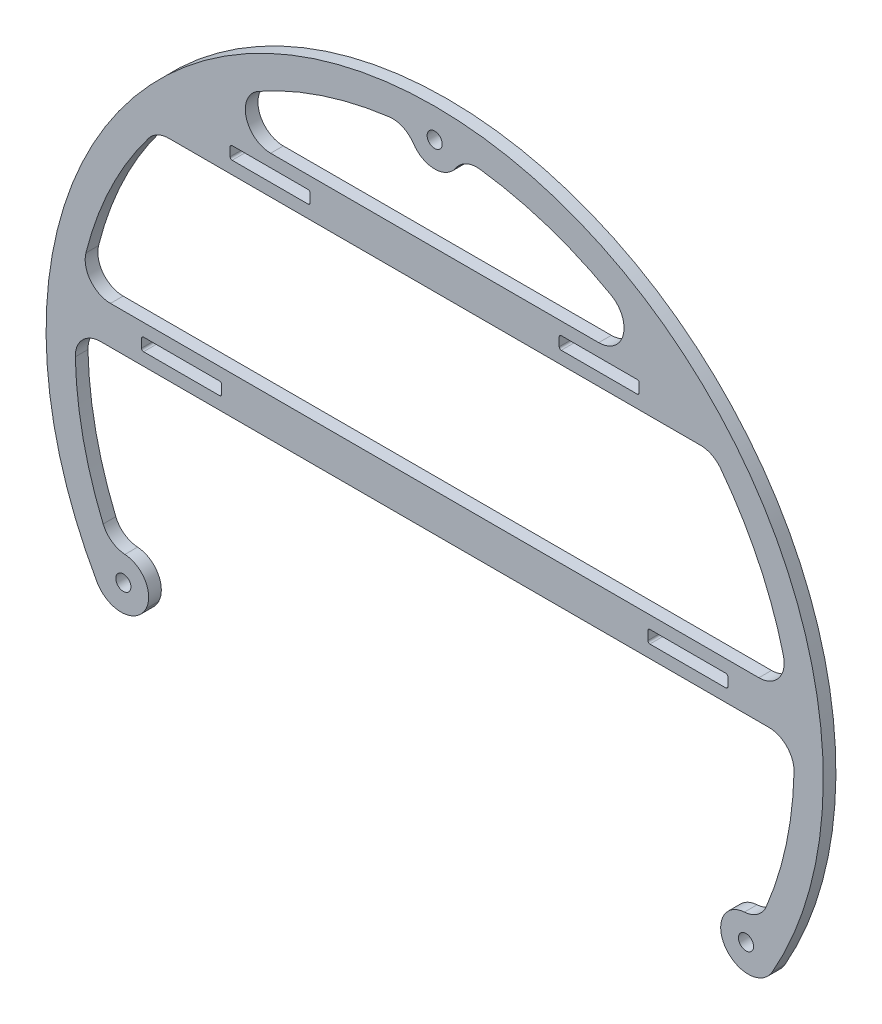
SolidWorks part; units mm, degrees
ref_plane "Front Plane" through (0, 0, 0) normal (0, 0, 1) x (1, 0, 0)
ref_plane "Top Plane" through (0, 0, 0) normal (0, 1, 0) x (1, 0, 0)
ref_plane "Right Plane" through (0, 0, 0) normal (1, 0, 0) x (0, 0, -1)
sketch "Sketch1" plane through (0, 0, 0) normal (0, 0, 1) x (1, 0, 0)
  circle A0 centre (0, 0) radius 97.4725
  circle A1 centre (0, 0) radius 90.17
  dimension "D1" = 194.945
  dimension "D2" = 180.34
extrude "Boss-Extrude1" add sketch "Sketch1" along normal blind 3.175
sketch "Sketch2" plane through (0, 0, 3.175) normal (0, 0, 1) x (1, 0, 0)
  arc A5 (-5.2915, 86.6596) -> (5.2915, 86.6596) centre (0, 90.17) ccw
  circle A6 centre (0, 0) radius 90.17 construction
  arc A8 (-5.2915, 86.6596) -> (-11.3847, 89.4484) centre (-10.5829, 83.1492) ccw
  arc A9 (5.2915, 86.6596) -> (11.3847, 89.4484) centre (10.5829, 83.1492) cw
  arc A10 (11.3847, 89.4484) -> (-11.3847, 89.4484) centre (0, 0) ccw
  dimension "D3" = 6.35
  dimension "D4" = 6.35
extrude "Boss-Extrude2" add sketch "Sketch2" against normal up to surface (3.175 mm away) up to face at (97.4725, 0, 0)
hole_wizard "#6 Clearance Hole2" positions "Sketch8" profile "Sketch7" hole size "#6" standard "ANSI Inch"
sketch "Sketch8" plane through (0, 0, 0) normal (0, 0, -1) x (-1, 0, 0)
  point P0 (0, 90.17)
sketch "Sketch7" plane through (0, 90.17, 0) normal (1, 0, 0) x (0, 1, 0)
  line L0 (0, 0) -> (0, 7.4908)
  line L1 (0, 7.4908) -> (1.8986, 6.35)
  line L2 (1.8986, 6.35) -> (1.8986, 0)
  line L5 (1.8986, 0) -> (0, 0)
  line L10 (0, 7.4908) -> (-1.8987, 6.35) construction
  line L11 (0, -6.35) -> (0, 107.95) construction
  dimension "Hole Dia." = 3.7973
  dimension "Hole Depth" = 6.35
  dimension "Drill Angle" = 118
pattern_circular "CirPattern2" count 3 over 360 about axis through (0, 0, 0) along (0, 0, 1) of "#6 Clearance Hole2", "Boss-Extrude2"
sketch "Sketch14" plane through (0, 0, 3.175) normal (0, 0, 1) x (1, 0, 0)
  arc A0 (-72.4037, -47.9124) -> (-84.6871, -48.2595) centre (-78.6379, -44.8123) cw
  circle A1 centre (0, 0) radius 97.4725 construction
  arc A2 (-72.4037, -47.9124) -> (-77.6952, -38.7473) centre (-78.0895, -45.085) ccw construction
  arc A3 (72.4037, -47.9124) -> (84.6871, -48.2595) centre (78.6379, -44.8123) ccw
  arc A4 (77.6952, -38.7473) -> (72.4037, -47.9124) centre (78.0895, -45.085) ccw construction
  arc A5 (71.7723, -54.5836) -> (72.4037, -47.9124) centre (66.7179, -50.7397) ccw construction
  arc A6 (-71.7723, -54.5836) -> (71.7723, -54.5836) centre (0, 0) ccw construction
  arc A7 (-72.4037, -47.9124) -> (-71.7723, -54.5836) centre (-66.7179, -50.7397) ccw construction
  arc A8 (-84.6871, -48.2595) -> (84.6871, -48.2595) centre (0, 0) ccw
  arc A9 (71.7723, -54.5836) -> (72.4037, -47.9124) centre (66.7179, -50.7397) ccw
  arc A10 (-71.7723, -54.5836) -> (71.7723, -54.5836) centre (0, 0) ccw
  arc A11 (-72.4037, -47.9124) -> (-71.7723, -54.5836) centre (-66.7179, -50.7397) ccw
extrude "Cut-Extrude1" cut sketch "Sketch14" against normal through all
sketch "Sketch13" plane through (0, 0, 3.175) normal (0, 0, 1) x (1, 0, 0)
  line L0 (-90.0604, 4.445) -> (90.0604, 4.445)
  line L1 (-89.0812, 13.97) -> (89.0812, 13.97)
  line L2 (0, 0) -> (0, 50000) construction
  line L4 (-73.533, 10.795) -> (-53.467, 10.795)
  line L5 (-73.533, 10.795) -> (-73.533, 7.62)
  line L6 (-73.533, 7.62) -> (-53.467, 7.62)
  line L7 (-53.467, 10.795) -> (-53.467, 7.62)
  line L8 (53.467, 10.795) -> (73.533, 10.795)
  line L9 (53.467, 10.795) -> (53.467, 7.62)
  line L10 (53.467, 7.62) -> (73.533, 7.62)
  line L11 (73.533, 10.795) -> (73.533, 7.62)
  arc A0 (-11.3847, 89.4484) -> (-83.1569, -34.8648) centre (0, 0) ccw construction
  arc A1 (83.1569, -34.8648) -> (11.3847, 89.4484) centre (0, 0) ccw construction
  arc A2 (-89.0812, 13.97) -> (-90.0604, 4.445) centre (0, 0) ccw
  arc A3 (90.0604, 4.445) -> (89.0812, 13.97) centre (0, 0) ccw
  point P17 (-63.5, 10.795)
  point P20 (63.5, 10.795)
  dimension "D1" = 9.525
  dimension "D2" = 4.445
  dimension "D3" = 3.175
  dimension "D4" = 3.175
  dimension "D5" = 127
  dimension "D6" = 20.066
extrude "Boss-Extrude5" add sketch "Sketch13" against normal up to surface (3.175 mm away) up to face at (76.1909, -45.085, 0)
sketch "Sketch17" plane through (0, 0, 3.175) normal (0, 0, 1) x (1, 0, 0)
  line L0 (-60.7048, 66.675) -> (60.7048, 66.675)
  line L1 (-69.746, 57.15) -> (69.746, 57.15)
  line L2 (0, 57.15) -> (0, 66.675) construction
  line L3 (-51.308, 63.5) -> (-31.242, 63.5)
  line L4 (-51.308, 63.5) -> (-51.308, 60.325)
  line L5 (-51.308, 60.325) -> (-31.242, 60.325)
  line L6 (-31.242, 63.5) -> (-31.242, 60.325)
  line L7 (31.242, 63.5) -> (51.308, 63.5)
  line L8 (31.242, 63.5) -> (31.242, 60.325)
  line L9 (31.242, 60.325) -> (51.308, 60.325)
  line L10 (51.308, 63.5) -> (51.308, 60.325)
  arc A0 (-11.3847, 89.4484) -> (-89.0812, 13.97) centre (0, 0) ccw construction
  arc A1 (89.0812, 13.97) -> (11.3847, 89.4484) centre (0, 0) ccw construction
  arc A3 (-60.7048, 66.675) -> (-69.746, 57.15) centre (0, 0) ccw
  arc A4 (69.746, 57.15) -> (60.7048, 66.675) centre (0, 0) ccw
  point P10 (-41.275, 63.5)
  point P11 (41.275, 63.5)
  dimension "D1" = 9.525
  dimension "D2" = 57.15
  dimension "D3" = 20.066
  dimension "D4" = 82.55
  dimension "D5" = 3.175
  dimension "D6" = 3.175
extrude "Boss-Extrude6" add sketch "Sketch17" against normal up to surface (3.175 mm away) up to face at (0, -19.181, 0)
fillet "Fillet1" radius 6.35 8 edges at (90.0604, 4.445, 1.5875) (-90.0604, 4.445, 1.5875) (-89.0812, 13.97, 1.5875) (89.0812, 13.97, 1.5875) (69.746, 57.15, 1.5875) (-69.746, 57.15, 1.5875) (-60.7048, 66.675, 1.5875) (60.7048, 66.675, 1.5875)
fillet "Fillet2" radius 0.508 16 edges at (-73.533, 7.62, 1.5875) (-73.533, 10.795, 1.5875) (-53.467, 10.795, 1.5875) (-53.467, 7.62, 1.5875) (53.467, 10.795, 1.5875) (53.467, 7.62, 1.5875) (73.533, 7.62, 1.5875) (73.533, 10.795, 1.5875) (31.242, 63.5, 1.5875) (31.242, 60.325, 1.5875) (51.308, 60.325, 1.5875) (51.308, 63.5, 1.5875) (-31.242, 60.325, 1.5875) (-31.242, 63.5, 1.5875) (-51.308, 60.325, 1.5875) (-51.308, 63.5, 1.5875)
